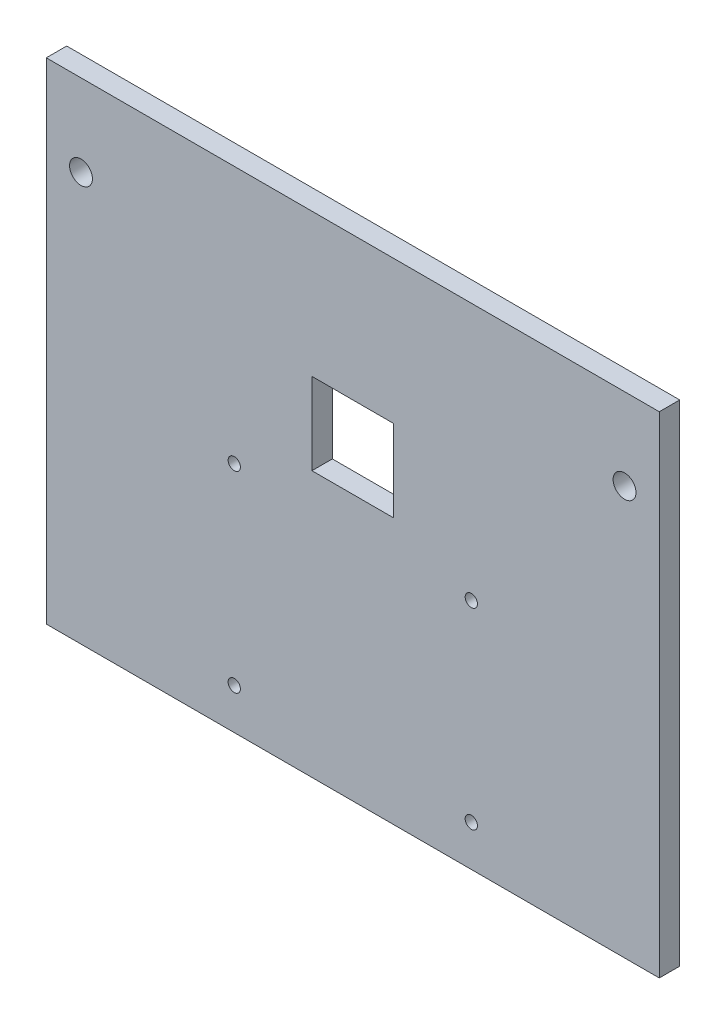
SolidWorks part; units mm, degrees
ref_plane "Plan de face" through (0, 0, 0) normal (0, 0, 1) x (1, 0, 0)
ref_plane "Plan de dessus" through (0, 0, 0) normal (0, 1, 0) x (1, 0, 0)
ref_plane "Plan de droite" through (0, 0, 0) normal (1, 0, 0) x (0, 0, -1)
sketch "Esquisse1" plane through (0, 0, 0) normal (0, 0, 1) x (1, 0, 0)
  line L0 (46, -63) -> (104, -63) construction
  line L1 (0, 0) -> (150, 0)
  line L2 (0, 0) -> (0, -120)
  line L3 (0, -120) -> (150, -120)
  line L4 (150, 0) -> (150, -120)
  line L5 (65, -35) -> (85, -35)
  line L6 (65, -35) -> (65, -55)
  line L7 (65, -55) -> (85, -55)
  line L8 (85, -35) -> (85, -55)
  line L9 (104, -63) -> (104, -110) construction
  line L10 (104, -110) -> (46, -110) construction
  line L11 (46, -110) -> (46, -63) construction
  line L12 (8.5, -20) -> (141.5, -20) construction
  circle A0 centre (46, -63) radius 1.5
  circle A1 centre (104, -63) radius 1.5
  circle A2 centre (104, -110) radius 1.5
  circle A3 centre (46, -110) radius 1.5
  circle A4 centre (8.5, -20) radius 2.8
  circle A5 centre (141.5, -20) radius 2.8
  dimension "D6" = 3
  dimension "D11" = 5.6
  dimension "D1" = 150
  dimension "D2" = 120
  dimension "D3" = 20
  dimension "D4" = 35
  dimension "D5" = 65
  dimension "D7" = 47
  dimension "D8" = 58
  dimension "D9" = 10
  dimension "D10" = 46
  dimension "D12" = 8.5
  dimension "D13" = 8.5
  dimension "D14" = 20
  dimension "D15" = 20
extrude "Boss.-Extru.1" add sketch "Esquisse1" along normal blind 5
